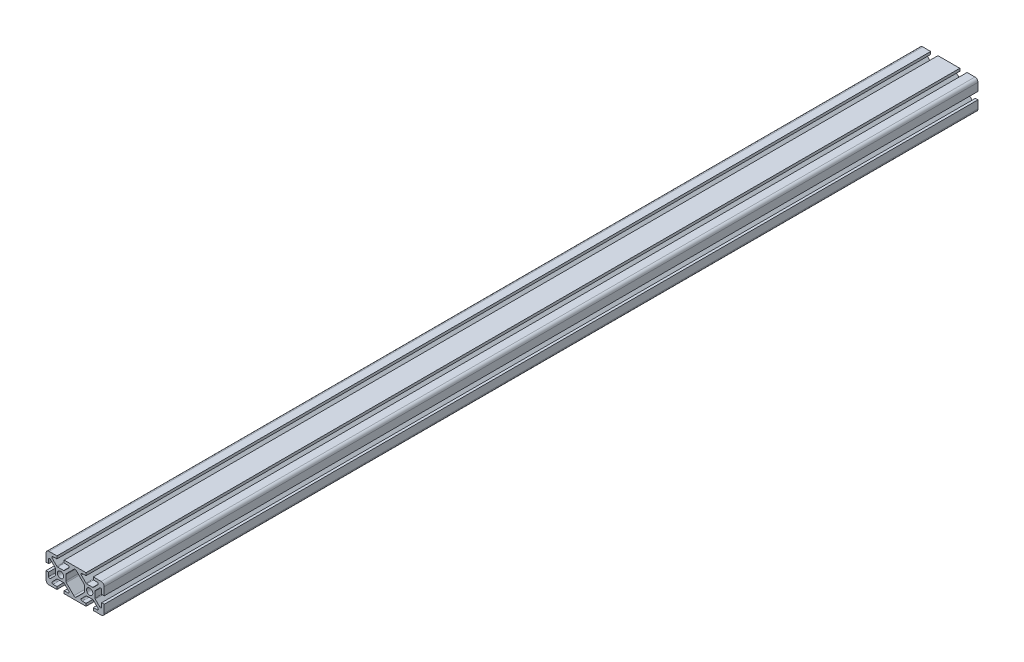
SolidWorks part; units mm, degrees
material "6063-T6"
ref_plane "Front Plane" through (0, 0, 0) normal (0, 0, 1) x (1, 0, 0)
ref_plane "Top Plane" through (0, 0, 0) normal (0, 1, 0) x (1, 0, 0)
ref_plane "Right Plane" through (0, 0, 0) normal (1, 0, 0) x (0, 0, -1)
sketch "Sketch1" plane through (0, 0, 0) normal (0, 0, 1) x (1, 0, 0)
  line L0 (10, 10) -> (10, -10) construction
  line L1 (-20, 0) -> (20, 0) construction
  line L2 (12.5, -10) -> (20, -10)
  line L3 (20, -10) -> (20, -2.5)
  line L4 (12.5, -10) -> (12.5, -8.2134)
  line L5 (12.5, -8.2134) -> (16.95, -8.2134)
  line L6 (16.95, -8.2134) -> (12.3366, -3.6)
  line L7 (10, 0) -> (20, -10) construction
  line L8 (20, -2.5) -> (18.2134, -2.5)
  line L9 (18.2134, -2.5) -> (18.2134, -6.95)
  line L10 (18.2134, -6.95) -> (13.6, -2.3366)
  line L11 (15.9067, -4.6433) -> (14.6433, -5.9067) construction
  line L12 (0, 10) -> (0, -10) construction
  line L13 (0, -10) -> (-20, -10) construction
  line L14 (-10, 10) -> (10, 10) construction
  line L15 (20, 2.5) -> (20, -2.5) construction
  circle A0 centre (10, 0) radius 2.15
  arc A1 (15.5015, -8.2134) -> (15.9257, -7.1891) centre (15.5015, -7.6134) ccw construction
  point P8 (10, -3.6)
  point P16 (15.275, -5.275)
  point P30 (20, 0)
  dimension "Center Hole Diameter" = 4.3
  dimension "D3" = 0.6
  dimension "Rail Width" = 20
  dimension "T-Slot Width" = 5
  dimension "Slot Depth" = 6.4
  dimension "Rail Height" = 40
  dimension "Inner Slot Width" = 13.9
  dimension "Hole Spacing" = 20
sketch "Sketch2" plane through (0, 0, 0) normal (1, 0, 0) x (0, 0, -1)
  line L0 (-300, -10) -> (300, -10) construction
  line L1 (-260, 0) -> (260, 0) construction
  point P6 (-260, 0)
  point P8 (260, 0)
  dimension "Length" = 600
  dimension "D1" = 40
sketch "Sketch3" plane through (0, 0, 0) normal (0, 0, 1) x (1, 0, 0)
  line L0 (12.5, -10) -> (17.9, -10)
  line L1 (12.5, -10) -> (20, -10) construction
  line L2 (12.5, -10) -> (12.5, -8.2134) construction
  line L3 (12.5, -8.2134) -> (16.95, -8.2134) construction
  line L4 (12.5, -8.2134) -> (12.5, -10)
  line L5 (12.5, -8.2134) -> (16.95, -8.2134)
  line L6 (10, -3.6) -> (12.3366, -3.6)
  line L7 (16.95, -8.2134) -> (12.3366, -3.6) construction
  line L8 (12.3366, -3.6) -> (16.95, -8.2134)
  line L9 (20, -10) -> (20, -2.5) construction
  line L10 (18.2134, -6.95) -> (13.6, -2.3366) construction
  line L11 (18.2134, -2.5) -> (18.2134, -6.95) construction
  line L12 (18.2134, -6.95) -> (18.2134, -2.5)
  line L13 (20, -2.5) -> (18.2134, -2.5) construction
  line L14 (18.2134, -2.5) -> (20, -2.5)
  line L15 (20, -2.5) -> (20, -7.9)
  line L16 (18.2134, -6.95) -> (13.6, -2.3366)
  line L17 (13.6, 0) -> (13.6, -2.3366)
  line L18 (-20, 0) -> (20, 0) construction
  line L19 (10, -3.6) -> (10, -2.15)
  line L20 (10, 10) -> (10, -10) construction
  line L21 (13.6, 0) -> (12.15, 0)
  arc A5 (17.9, -10) -> (20, -7.9) centre (17.9, -7.9) ccw
  circle A10 centre (10, 0) radius 2.15 construction
  arc A11 (10, -2.15) -> (12.15, 0) centre (10, 0) ccw
  dimension "D1" = 2.1
extrude "Boss-Extrude1" add sketch "Sketch3" along normal mid plane 600
sketch "Sketch4" plane through (0, 0, 0) normal (0, 0, 1) x (1, 0, 0)
  line L0 (10, -3.6) -> (7.6634, -3.6)
  line L4 (7.6634, -3.6) -> (3.05, -8.2134)
  line L5 (3.05, -8.2134) -> (7.5, -8.2134)
  line L6 (7.5, -8.2134) -> (7.5, -10)
  line L18 (7.5, -10) -> (0, -10)
  line L19 (12.5, -10) -> (12.5, -8.2134) construction
  line L20 (12.5, -8.2134) -> (16.95, -8.2134) construction
  line L21 (10, -3.6) -> (12.3366, -3.6) construction
  line L22 (16.95, -8.2134) -> (12.3366, -3.6) construction
  line L23 (0, -8.7366) -> (6.4, -2.3366)
  line L24 (0, 10) -> (0, -10) construction
  line L25 (6.4, -2.3366) -> (6.4, 0)
  line L26 (-20, 0) -> (20, 0) construction
  line L27 (6.4, 0) -> (7.85, 0)
  line L28 (13.6, 0) -> (12.15, 0) construction
  line L29 (0, -8.7366) -> (0, -10)
  line L30 (10, -2.15) -> (10, -3.6)
  circle A4 centre (10, 0) radius 2.15 construction
  arc A5 (7.85, 0) -> (10, -2.15) centre (10, 0) ccw
extrude "Boss-Extrude2" add sketch "Sketch4" along normal mid plane 600
mirror "Mirror1" about plane through (0, 0, 0) normal (1, 0, 0) of bodies 137 134
mirror "Mirror2" about plane through (0, 0, 0) normal (0, 1, 0) of bodies 135
fillet "Fillet1" radius 0.75 24 edges at (-7.6634, -3.6, 0) (-12.3366, -3.6, 0) (12.3366, -3.6, 0) (7.6634, -3.6, 0) (-3.05, -8.2134, 0) (-18.2134, -6.95, 0) (-16.95, -8.2134, 0) (-13.6, -2.3366, 0) (-18.2134, 6.95, 0) (-16.95, 8.2134, 0) (-12.3366, 3.6, 0) (-7.6634, 3.6, 0) (-13.6, 2.3366, 0) (-3.05, 8.2134, 0) (3.05, 8.2134, 0) (13.6, -2.3366, 0) (18.2134, 6.95, 0) (13.6, 2.3366, 0) (7.6634, 3.6, 0) (12.3366, 3.6, 0) (16.95, 8.2134, 0) (18.2134, -6.95, 0) (16.95, -8.2134, 0) (3.05, -8.2134, 0)
fillet "Fillet2" radius 1.25 6 edges at (0, -8.7366, 0) (-6.4, -2.3366, 0) (-6.4, 2.3366, 0) (6.4, -2.3366, 0) (6.4, 2.3366, 0) (0, 8.7366, 0)
equation "\"D1@Sketch3\" = \"D3@Sketch1\" * 3.5"
equation "\"D1@Boss-Extrude1\" = \"Length@Sketch2\""
equation "\"D1@Boss-Extrude2\" = \"Length@Sketch2\""
equation "\"D1@Sketch2\"=\"Rail Height@Sketch1\""
